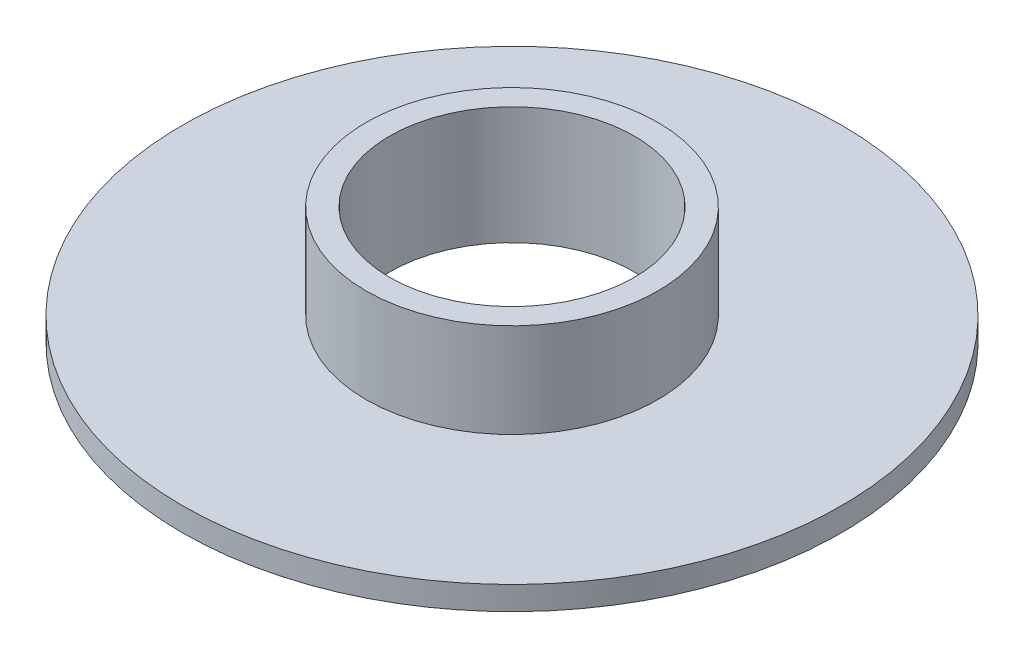
SolidWorks part; units mm, degrees
ref_plane "Front Plane" through (0, 0, 0) normal (0, 0, 1) x (1, 0, 0)
ref_plane "Top Plane" through (0, 0, 0) normal (0, 1, 0) x (1, 0, 0)
ref_plane "Right Plane" through (0, 0, 0) normal (1, 0, 0) x (0, 0, -1)
sketch "Sketch1" plane through (0, 0, 0) normal (1, 0, 0) x (0, 0, -1)
  line L0 (0, 0) -> (70, 0)
  line L1 (70, 0) -> (70, 5)
  line L2 (70, 5) -> (31, 5)
  line L3 (31, 5) -> (31, 25)
  line L4 (31, 25) -> (26, 25)
  line L5 (26, 25) -> (26, 5)
  line L6 (26, 5) -> (0, 5)
  line L7 (0, 5) -> (0, 0)
  dimension "D1" = 5
  dimension "D2" = 31
  dimension "D3" = 70
  dimension "D4" = 5
  dimension "D5" = 20
revolve "Revolve1" add sketch "Sketch1" angle 360 about L7
sketch "Sketch3" plane through (0, 5, 0) normal (0, 1, 0) x (1, 0, 0)
  circle A0 centre (0, 0) radius 26
extrude "Cut-Extrude1" cut sketch "Sketch3" against normal blind 10
